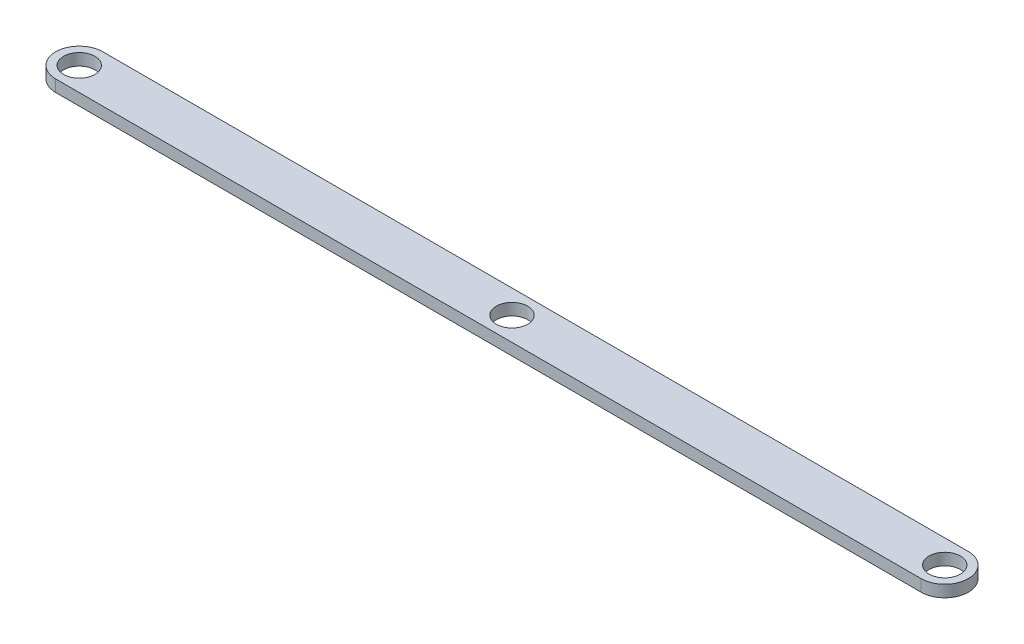
SolidWorks part; units mm, degrees
material "6061 Alloy"
ref_plane "Front" through (0, 0, 0) normal (0, 0, 1) x (1, 0, 0)
ref_plane "Top" through (0, 0, 0) normal (0, 1, 0) x (1, 0, 0)
ref_plane "Right" through (0, 0, 0) normal (1, 0, 0) x (0, 0, -1)
sketch "Sketch1" plane through (0, 0, 0) normal (0, 1, 0) x (1, 0, 0)
  line L0 (-87.5, 0) -> (87.5, 0)
  line L1 (-87.5, -4.7625) -> (87.5, -4.7625)
  line L2 (-87.5, 4.7625) -> (87.5, 4.7625)
  arc A0 (-87.5, -4.7625) -> (-87.5, 4.7625) centre (-87.5, 0) cw
  arc A1 (87.5, -4.7625) -> (87.5, 4.7625) centre (87.5, 0) ccw
  circle A2 centre (-87.5, 0) radius 3.175
  circle A3 centre (87.5, 0) radius 3.175
  circle A4 centre (0, 0) radius 3.175
  point P4 (0, 0)
  dimension "D4" = 6.35
  dimension "D5" = 6.35
  dimension "D1" = 175
  dimension "D2" = 4.7625
  dimension "D3" = 4.7625
extrude "Boss-Extrude1" add sketch "Sketch1" along normal blind 2.3813
